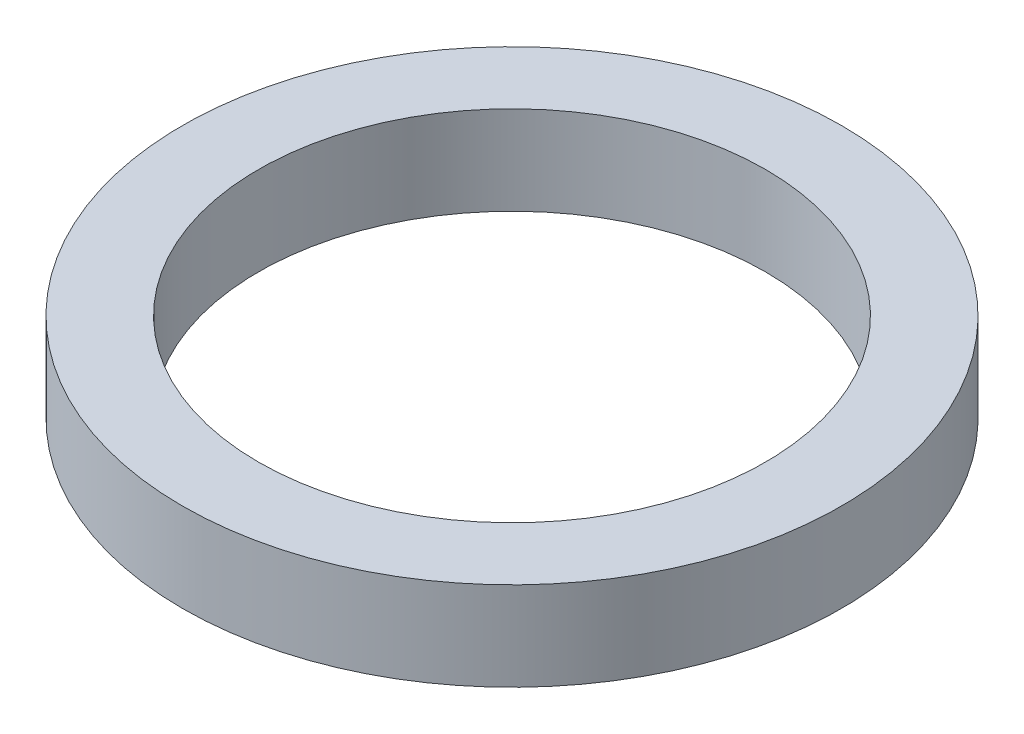
SolidWorks part; units mm, degrees
ref_plane "Front" through (0, 0, 0) normal (0, 0, 1) x (1, 0, 0)
ref_plane "Top" through (0, 0, 0) normal (0, 1, 0) x (1, 0, 0)
ref_plane "Right" through (0, 0, 0) normal (1, 0, 0) x (0, 0, -1)
sketch "Sketch1" plane through (0, 0, 0) normal (0, 1, 0) x (1, 0, 0)
  circle A0 centre (0, 0) radius 26
  circle A1 centre (0, 0) radius 20
  dimension "D1" = 40
  dimension "D2" = 52
extrude "Boss-Extrude1" add sketch "Sketch1" along normal blind 7
